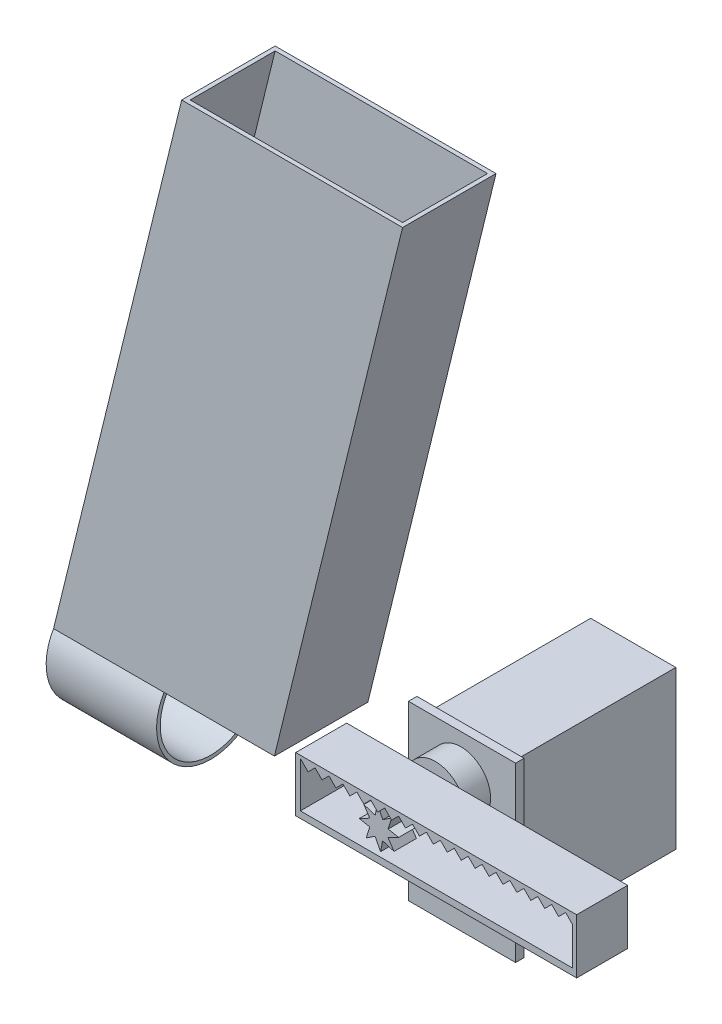
SolidWorks part; units mm, degrees
ref_plane "前视基准面" through (0, 0, 0) normal (0, 0, 1) x (1, 0, 0)
ref_plane "上视基准面" through (0, 0, 0) normal (0, 1, 0) x (1, 0, 0)
ref_plane "右视基准面" through (0, 0, 0) normal (1, 0, 0) x (0, 0, -1)
sketch "草图1" plane through (0, 0, 0) normal (0, 1, 0) x (1, 0, 0)
  line L1 (-12.5, 5) -> (12.5, 5)
  line L2 (-12.5, 5) -> (-12.5, -5)
  line L3 (-12.5, -5) -> (12.5, -5)
  line L4 (12.5, 5) -> (12.5, -5)
  line L5 (-12.5, 5) -> (12.5, -5) construction
  line L6 (-12.5, -5) -> (12.5, 5) construction
  line L7 (-13, 5.5) -> (13, 5.5)
  line L8 (-13, 5.5) -> (-13, -5.5)
  line L9 (-13, -5.5) -> (13, -5.5)
  line L10 (13, 5.5) -> (13, -5.5)
  line L11 (-13, 5.5) -> (13, -5.5) construction
  line L12 (-13, -5.5) -> (13, 5.5) construction
  point P0 (0, 0)
  point P7 (0, 0)
sketch "草图2" plane through (0, 0, 0) normal (0, 0, 1) x (1, 0, 0)
  line L0 (0, 0) -> (15.0814, 61.4271)
sketch3d "3D草图1"
  line L0 (0, 0, 0) -> (15.0814, 61.4271, 0) construction
  line L1 (0, 0, 0) -> (15.0814, 61.4271, 0)
sweep "扫描1" add profiles "草图1" path "草图2"
sketch "草图3" plane through (0, 0, 0) normal (1, 0, 0) x (0, 0, -1)
  line L0 (-5.5, 0) -> (5.5, 0) construction
  line L1 (-5.5, 0) -> (-5, 0)
  line L2 (5, 0) -> (5.5, 0)
  arc A0 (-5, 0) -> (5, 0) centre (0, -3.2154) ccw
  arc A1 (-5.5, 0) -> (5.5, 0) centre (0, -3.2154) ccw
extrude "凸台-拉伸1" add sketch "草图3" against normal blind 13
sketch "草图6" plane through (0, 0, 0) normal (0, 0, 1) x (1, 0, 0)
  line L0 (13, -0.8823) -> (13, -7.3304)
  line L1 (13, -7.3304) -> (46.0704, -7.3304)
  line L2 (46.0704, -7.3304) -> (46.0704, -0.8823)
  line L3 (13, -0.8823) -> (46.0704, -0.8823)
  line L4 (13.5533, -2.1251) -> (13.5533, -6.5545)
  line L5 (13.5533, -6.5545) -> (45.5905, -6.5545)
  line L6 (45.5905, -6.5545) -> (45.5905, -2.1251)
  line L7 (45.5905, -2.1251) -> (44.7714, -1.306)
  line L8 (44.7714, -1.306) -> (43.9522, -2.1251)
  line L9 (43.9522, -2.1251) -> (43.1331, -1.306)
  line L10 (43.1331, -1.306) -> (42.314, -2.1251)
  line L11 (42.314, -2.1251) -> (41.4948, -1.306)
  line L12 (41.4948, -1.306) -> (40.6757, -2.1251)
  line L13 (40.6757, -2.1251) -> (39.8566, -1.306)
  line L14 (39.8566, -1.306) -> (39.0374, -2.1251)
  line L15 (39.0374, -2.1251) -> (38.2183, -1.306)
  line L16 (38.2183, -1.306) -> (37.3992, -2.1251)
  line L17 (37.3992, -2.1251) -> (36.58, -1.306)
  line L18 (36.58, -1.306) -> (35.7609, -2.1251)
  line L19 (35.7609, -2.1251) -> (34.9418, -1.306)
  line L20 (34.9418, -1.306) -> (34.1226, -2.1251)
  line L21 (34.1226, -2.1251) -> (33.3035, -1.306)
  line L22 (33.3035, -1.306) -> (32.4844, -2.1251)
  line L23 (32.4844, -2.1251) -> (31.6653, -1.306)
  line L24 (31.6653, -1.306) -> (30.8461, -2.1251)
  line L25 (30.8461, -2.1251) -> (30.027, -1.306)
  line L26 (30.027, -1.306) -> (29.2079, -2.1251)
  line L27 (29.2079, -2.1251) -> (28.3887, -1.306)
  line L28 (28.3887, -1.306) -> (27.5696, -2.1251)
  line L29 (27.5696, -2.1251) -> (26.7505, -1.306)
  line L30 (26.7505, -1.306) -> (25.9313, -2.1251)
  line L31 (25.9313, -2.1251) -> (25.1122, -1.306)
  line L32 (25.1122, -1.306) -> (24.2931, -2.1251)
  line L33 (24.2931, -2.1251) -> (23.4739, -1.306)
  line L34 (23.4739, -1.306) -> (22.6548, -2.1251)
  line L35 (22.6548, -2.1251) -> (21.8357, -1.306)
  line L36 (21.8357, -1.306) -> (21.0165, -2.1251)
  line L37 (21.0165, -2.1251) -> (20.1974, -1.306)
  line L38 (20.1974, -1.306) -> (19.3783, -2.1251)
  line L39 (19.3783, -2.1251) -> (18.5591, -1.306)
  line L40 (18.5591, -1.306) -> (17.74, -2.1251)
  line L41 (17.74, -2.1251) -> (16.9209, -1.306)
  line L42 (16.9209, -1.306) -> (16.1017, -2.1251)
  line L43 (16.1017, -2.1251) -> (15.2826, -1.306)
  line L44 (15.2826, -1.306) -> (14.4635, -2.1251)
  line L45 (14.4635, -2.1251) -> (13.5533, -1.215)
  line L46 (13.5533, -2.1251) -> (13.5533, -1.215)
  point P0 (13, -0.8823)
  point P1 (13, -7.3304)
  point P2 (46.0704, -7.3304)
  point P3 (46.0704, -0.8823)
extrude "凸台-拉伸3" add sketch "草图6" along normal blind 3 and the other way blind 3 separate body
sketch "草图7" plane through (0, 0, 0) normal (0, 0, 1) x (1, 0, 0)
  line L0 (22.2452, -1.7156) -> (22.9012, -2.9615)
  line L1 (22.6548, -2.1251) -> (21.8357, -1.306) construction
  line L2 (22.2452, -1.7156) -> (22.0094, -2.9491)
  line L3 (22.4729, -1.6817) -> (22.9012, -2.9615) construction
  line L4 (23.9402, -2.256) -> (22.9012, -2.9615)
  line L5 (23.9402, -2.256) -> (23.5231, -3.6008)
  line L6 (24.7567, -3.8367) -> (23.5231, -3.6008)
  line L7 (24.7567, -3.8367) -> (23.5107, -4.4927)
  line L8 (24.2162, -5.5317) -> (23.5107, -4.4927)
  line L9 (24.2162, -5.5317) -> (22.8714, -5.1146)
  line L10 (22.6355, -6.3481) -> (22.8714, -5.1146)
  line L11 (22.6355, -6.3481) -> (21.9795, -5.1022)
  line L12 (20.9405, -5.8077) -> (21.9795, -5.1022)
  line L13 (20.9405, -5.8077) -> (21.3577, -4.4629)
  line L14 (20.1241, -4.227) -> (21.3577, -4.4629)
  line L15 (20.1241, -4.227) -> (21.37, -3.571)
  line L16 (20.6645, -2.532) -> (21.37, -3.571)
  line L17 (20.6645, -2.532) -> (22.0094, -2.9491)
  point P10 (22.4404, -4.0319)
  point P32 (22.4404, -4.0319)
  dimension "D2" = 1.3496
  dimension "D1" = 2
  dimension "D3" = 8
extrude "凸台-拉伸11" add sketch "草图7" along normal blind 2.6413 separate body
sketch "草图9" plane through (0, 0, 0) normal (0, 0, 1) x (1, 0, 0)
  circle A0 centre (22.4445, -4.0708) radius 0.8
extrude "凸台-拉伸12" add sketch "草图9" against normal blind 4
sketch "草图10" plane through (0, 0, 0) normal (0, 0, 1) x (1, 0, 0)
  circle A0 centre (22.4445, -4.0708) radius 3.5
extrude "凸台-拉伸13" add sketch "草图10" against normal blind 3 from surface at -4 starting at face at (23.2445, -4.0708, -4)
sketch "草图11" plane through (0, 0, 0) normal (0, 0, 1) x (1, 0, 0)
  line L1 (16.2733, 0.9793) -> (28.8862, 0.9793)
  line L2 (16.2733, 0.9793) -> (16.2733, -19.3496)
  line L3 (16.2733, -19.3496) -> (28.8862, -19.3496)
  line L4 (28.8862, 0.9793) -> (28.8862, -19.3496)
extrude "凸台-拉伸14" add sketch "草图11" against normal blind 1 from surface at -7 starting at face at (25.9445, -4.0708, -7)
sketch "草图12" plane through (0, 0, 0) normal (0, 0, 1) x (1, 0, 0)
  line L1 (17.5568, 0) -> (27.5808, 0)
  line L2 (17.5568, 0) -> (17.5568, -18.5468)
  line L3 (17.5568, -18.5468) -> (27.5808, -18.5468)
  line L4 (27.5808, 0) -> (27.5808, -18.5468)
extrude "凸台-拉伸15" add sketch "草图12" against normal blind 19.1623 from surface at -8 starting at face at (22.5797, -9.1852, -8)
